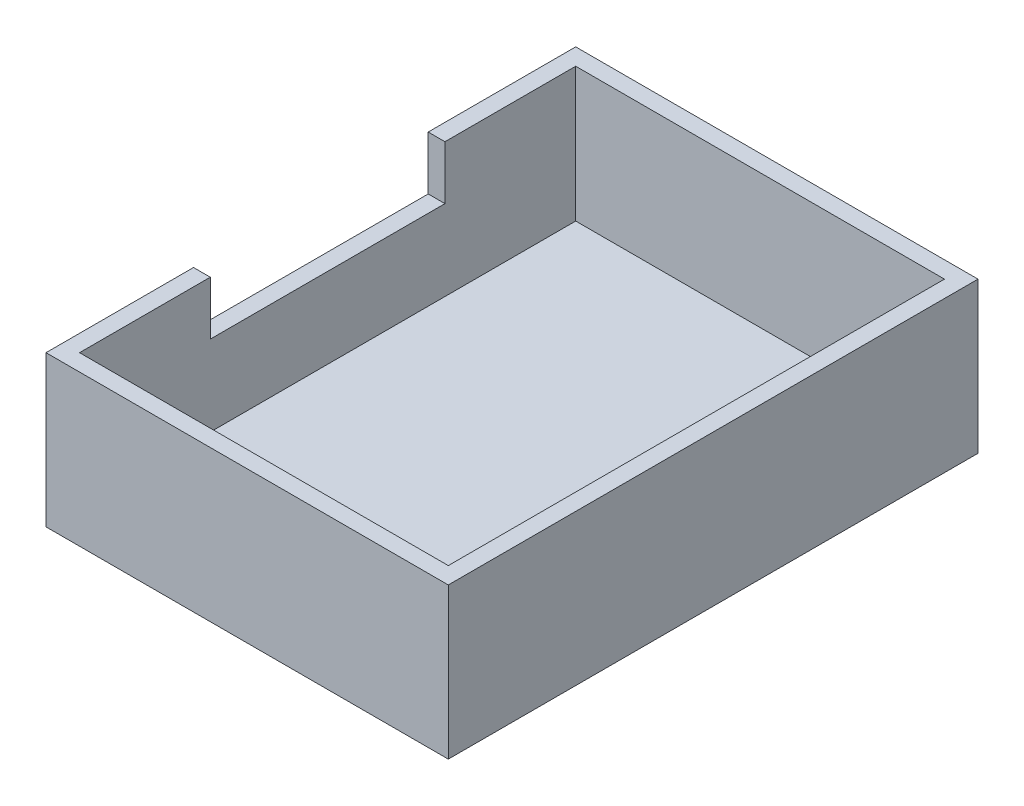
SolidWorks part; units mm, degrees
ref_plane "Frontal Plane" through (0, 0, 0) normal (0, 0, 1) x (1, 0, 0)
ref_plane "Horizontal Plane" through (0, 0, 0) normal (0, 1, 0) x (1, 0, 0)
ref_plane "Profile Plane" through (0, 0, 0) normal (1, 0, 0) x (0, 0, -1)
sketch "Sketch1" plane through (0, 0, 0) normal (0, 1, 0) x (1, 0, 0)
  line L0 (-60, 79) -> (60, 79)
  line L1 (-55, -74) -> (55, -74)
  line L2 (-55, -74) -> (-55, 74)
  line L3 (-55, 74) -> (55, 74)
  line L4 (55, -74) -> (55, 74)
  line L5 (-55, -74) -> (55, 74) construction
  line L6 (-55, 74) -> (55, -74) construction
  line L7 (60, -79) -> (60, 79)
  line L8 (-60, -79) -> (60, -79)
  line L9 (-60, -79) -> (-60, 79)
  point P0 (0, 0)
  dimension "D1" = 148
  dimension "D2" = 110
  dimension "D3" = 5
extrude "Boss-Extrude1" add sketch "Sketch1" along normal blind 40
sketch "Sketch2" plane through (0, 0, 0) normal (0, -1, 0) x (1, 0, 0)
  line L0 (-60, 79) -> (60, 79)
  line L1 (-60, 79) -> (60, 79)
  line L2 (60, 79) -> (60, -79)
  line L3 (60, 79) -> (60, -79)
  line L4 (60, -79) -> (-60, -79)
  line L5 (60, -79) -> (-60, -79)
  line L6 (-60, -79) -> (-60, 79)
  line L7 (-60, -79) -> (-60, 79)
extrude "Boss-Extrude2" add sketch "Sketch2" along normal blind 5
sketch "Sketch3" plane through (0, 40, 0) normal (0, 1, 0) x (1, 0, 0)
  line L0 (-60, 35) -> (-60, -35)
  line L1 (-60, 79) -> (-60, -79) construction
  line L2 (-60, -35) -> (-55, -35)
  line L3 (-55, 74) -> (-55, -74) construction
  line L4 (-55, -35) -> (-55, 35)
  line L5 (-55, 74) -> (-55, -74) construction
  line L6 (-55, 35) -> (-60, 35)
  point P0 (-66.6185, 23.3481)
  point P5 (-60, 0)
  dimension "D1" = 70
extrude "Cut-Extrude1" cut sketch "Sketch3" against normal offset from surface (16 mm away) 24 up to face at (0, 0, 0)
